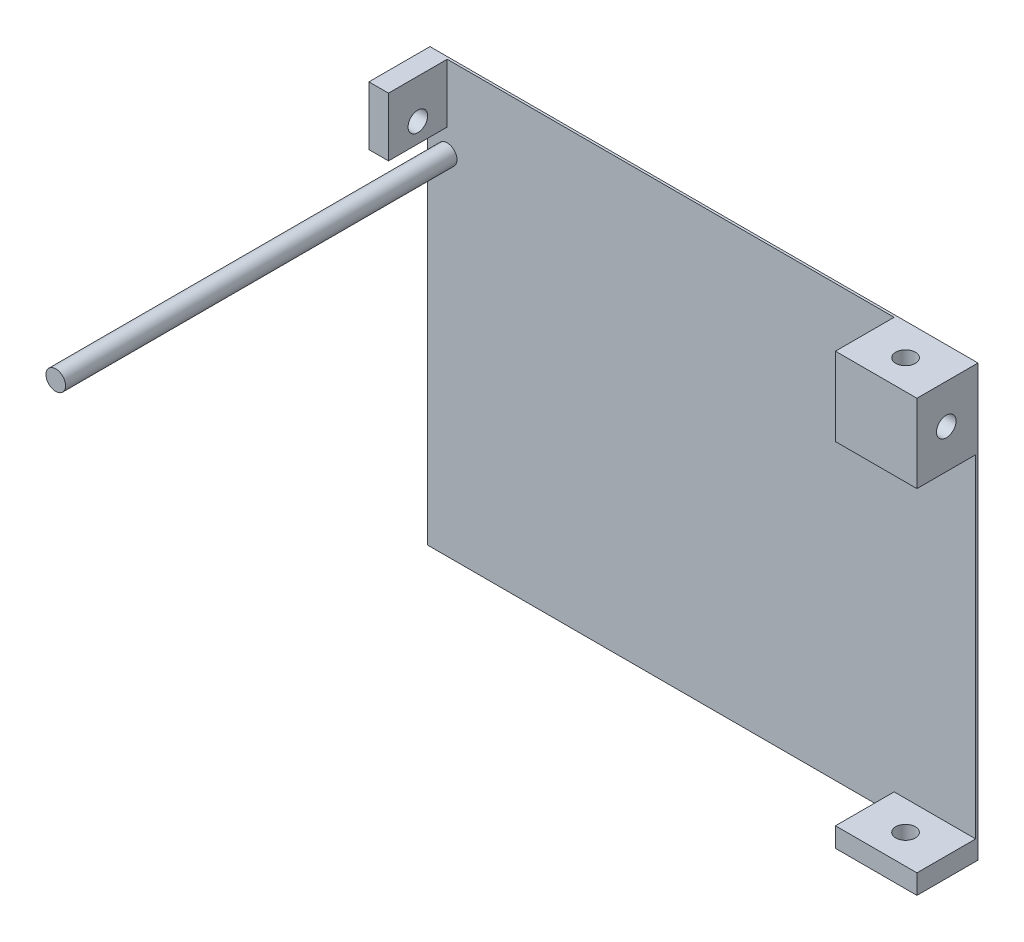
SolidWorks part; units mm, degrees
ref_plane "Alzado" through (0, 0, 0) normal (0, 0, 1) x (1, 0, 0)
ref_plane "Planta" through (0, 0, 0) normal (0, 1, 0) x (1, 0, 0)
ref_plane "Vista lateral" through (0, 0, 0) normal (1, 0, 0) x (0, 0, -1)
sketch "Croquis1" plane through (0, 0, 0) normal (0, 0, 1) x (1, 0, 0)
  line L1 (350, -275) -> (-350, -275)
  line L2 (350, -275) -> (350, 275)
  line L3 (350, 275) -> (-350, 275)
  line L4 (-350, -275) -> (-350, 275)
  line L5 (350, -275) -> (-350, 275) construction
  line L6 (350, 275) -> (-350, -275) construction
  point P0 (0, 0)
  dimension "D1" = 550
  dimension "D2" = 700
extrude "Saliente-Extruir1" add sketch "Croquis1" along normal blind 3
sketch "Croquis2" plane through (0, 0, 3) normal (0, 0, 1) x (1, 0, 0)
  line L0 (-350, -275) -> (350, -275) construction
  line L2 (350, 275) -> (350, 200)
  line L5 (-350, 275) -> (-325, 275)
  line L6 (-350, 275) -> (-350, 200)
  line L7 (-350, 200) -> (-325, 200)
  line L8 (-325, 275) -> (-325, 200)
  line L10 (350, 200) -> (350, 175)
  line L11 (350, 175) -> (245.9054, 175)
  line L13 (245.9054, -275) -> (350, -275)
  line L14 (245.9054, -275) -> (245.9054, -250)
  line L15 (245.9054, -250) -> (350, -250)
  line L16 (350, -275) -> (350, -250)
  line L17 (350, -275) -> (350, 275) construction
  line L18 (350, 275) -> (245.9054, 275)
  line L19 (350, 275) -> (-350, 275) construction
  line L20 (245.9054, 275) -> (245.9054, 175)
  dimension "D1" = 25
  dimension "D3" = 75
  dimension "D5" = 25
extrude "Saliente-Extruir2" add sketch "Croquis2" along normal blind 75
ref_plane "Plano1" through (-350, -275, 0) normal (1, 0, 0) x (0, 0, -1)
sketch "Croquis4" plane through (0, -275, 0) normal (0, -1, 0) x (1, 0, 0)
  line L0 (245.9054, 3) -> (350, 78) construction
  circle A0 centre (297.9527, 40.5) radius 12.5
  dimension "D1" = 25
extrude "Cortar-Extruir1" cut sketch "Croquis4" against normal blind 570
sketch "Croquis5" plane through (350, 0, 0) normal (1, 0, 0) x (0, 0, -1)
  line L0 (-3, 175) -> (-78, 275) construction
  circle A0 centre (-40.5, 225) radius 12.5
  dimension "D1" = 25
extrude "Cortar-Extruir2" cut sketch "Croquis5" against normal blind 740
sketch "Croquis7" plane through (0, 0, 3) normal (0, 0, 1) x (1, 0, 0)
  line L0 (-325, 200) -> (-325, 170) construction
  circle A0 centre (-325, 170) radius 12.5
  dimension "D2" = 25
  dimension "D1" = 30
extrude "Saliente-Extruir4" add sketch "Croquis7" along normal blind 500
